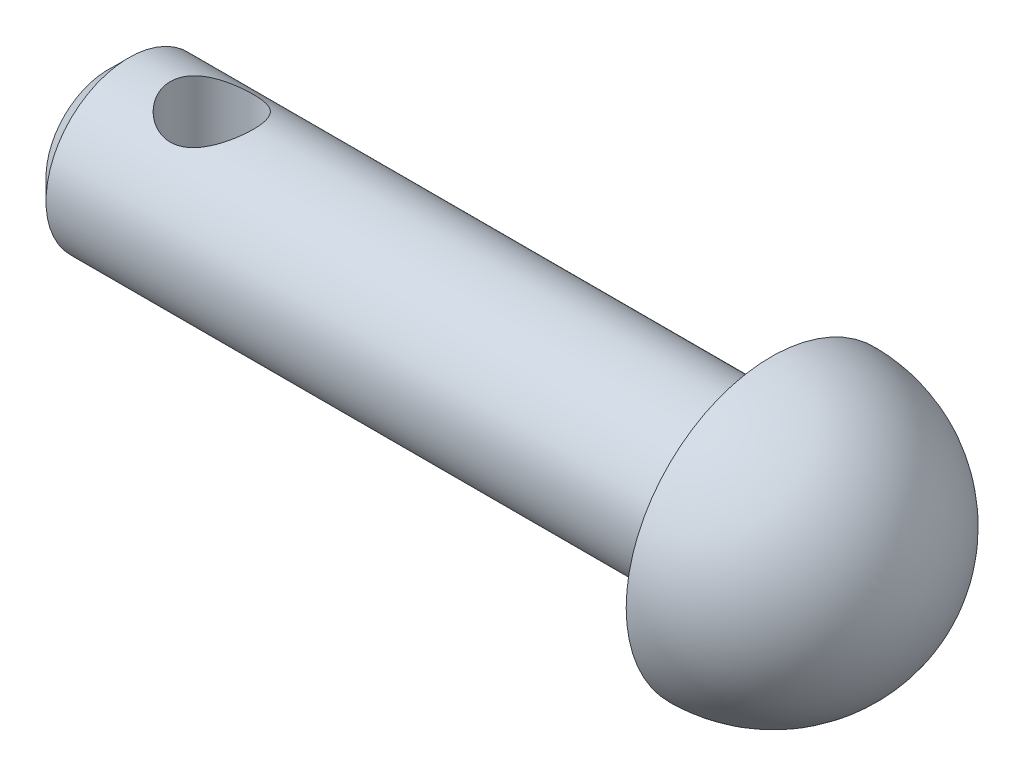
SolidWorks part; units mm, degrees
ref_plane "Front Plane" through (0, 0, 0) normal (0, 0, 1) x (1, 0, 0)
ref_plane "Top Plane" through (0, 0, 0) normal (0, 1, 0) x (1, 0, 0)
ref_plane "Right Plane" through (0, 0, 0) normal (1, 0, 0) x (0, 0, -1)
sketch "Sketch1" plane through (0, 0, 0) normal (1, 0, 0) x (0, 0, -1)
  circle A0 centre (0, 0) radius 2
  dimension "D1" = 4
extrude "Boss-Extrude1" add sketch "Sketch1" against normal blind 16
sketch "Sketch2" plane through (0, 0, 0) normal (0, 1, 0) x (1, 0, 0)
  line L0 (-16, 2) -> (-16, -2) construction
  circle A0 centre (-13.5, 0) radius 1
  dimension "D2" = 2
  dimension "D1" = 2.5
extrude "Cut-Extrude1" cut sketch "Sketch2" against normal through all both and the other way through all
sketch "Sketch3" plane through (0, 0, 0) normal (0, 1, 0) x (1, 0, 0)
  line L0 (-3.287, 0) -> (3.6, 0) construction
  line L1 (0, 0) -> (0, -3.5)
  line L2 (3.6, 0) -> (0, 0)
  arc A0 (0, -3.5) -> (3.6, 0) centre (0.0014, 0.1) ccw
  dimension "D2" = 3.6
  dimension "D1" = 3.5
  dimension "D3" = 3.6
revolve "Revolve1" add sketch "Sketch3" angle 360 about L0
chamfer "Chamfer1" distance 0.5 angle 45 1 edges at (-16, 0, -2)
